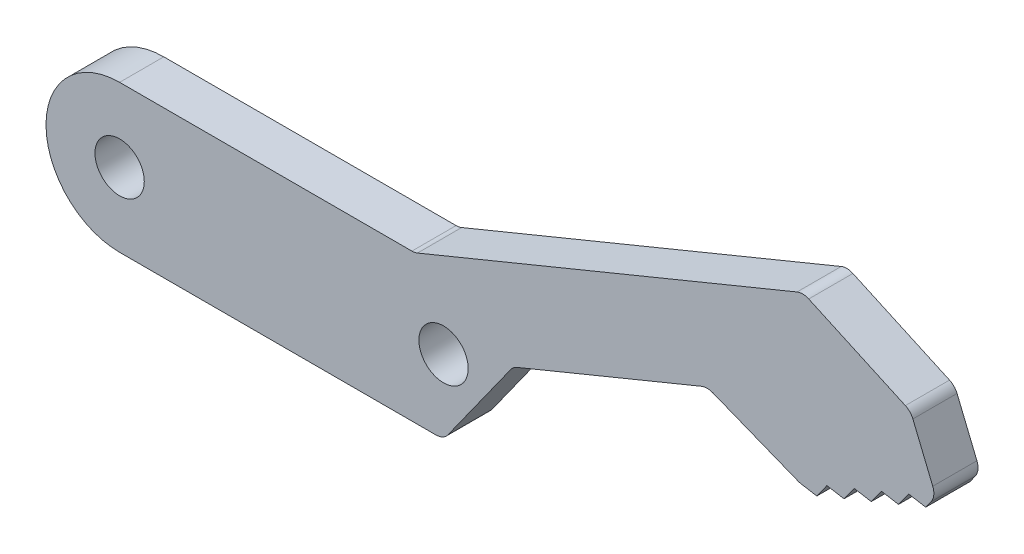
SolidWorks part; units mm, degrees
ref_plane "Front Plane" through (0, 0, 0) normal (0, 0, 1) x (1, 0, 0)
ref_plane "Top Plane" through (0, 0, 0) normal (0, 1, 0) x (1, 0, 0)
ref_plane "Right Plane" through (0, 0, 0) normal (1, 0, 0) x (0, 0, -1)
sketch "Sketch1" plane through (0, 0, 0) normal (0, 0, 1) x (1, 0, 0)
  line L0 (0, 0) -> (22, 0) construction
  line L1 (0, 5) -> (22, 5)
  line L2 (0, -5) -> (22, -5)
  line L3 (20.05, 5) -> (23.9914, -4.5863) construction
  line L4 (20.05, 5) -> (51.4959, 17.929) construction
  line L5 (23.9914, -4.5863) -> (55.4373, 8.3426) construction
  line L6 (51.4959, 17.929) -> (55.4373, 8.3426) construction
  line L7 (20.05, 5) -> (46.409, 15.8375)
  line L8 (46.409, 15.8375) -> (53.7261, 12.5046)
  line L9 (53.7261, 12.5046) -> (55.4373, 8.3426)
  line L10 (55.4373, 8.3426) -> (46.1885, 4.54) construction
  line L11 (46.1885, 4.54) -> (39.9002, 7.0361)
  line L12 (39.9002, 7.0361) -> (26.7299, 1.6211)
  line L13 (46.1885, 4.54) -> (47.351, 4.3422)
  line L14 (47.351, 4.3422) -> (48.0382, 5.3005)
  line L15 (47.351, 4.3422) -> (54.7501, 7.3843) construction
  line L16 (48.0382, 5.3005) -> (49.2008, 5.1027)
  line L17 (49.2008, 5.1027) -> (49.888, 6.0611)
  line L18 (49.888, 6.0611) -> (51.0505, 5.8633)
  line L19 (51.0505, 5.8633) -> (51.7378, 6.8216)
  line L20 (51.7378, 6.8216) -> (52.9003, 6.6238)
  line L21 (52.9003, 6.6238) -> (53.5875, 7.5821)
  line L22 (53.5875, 7.5821) -> (54.7501, 7.3843)
  line L23 (54.7501, 7.3843) -> (55.4373, 8.3426)
  line L24 (26.7299, 1.6211) -> (22, -5)
  arc A0 (0, 5) -> (0, -5) centre (0, 0) ccw
  arc A1 (22, -5) -> (22, 5) centre (22, 0) ccw
  circle A2 centre (0, 0) radius 1.675
  circle A3 centre (22, 0) radius 1.675
  point P3 (11, 0)
  dimension "D11" = 3.35
  dimension "D1" = 10
  dimension "D2" = 22
  dimension "D3" = 157.65
  dimension "D4" = 1.95
  dimension "D5" = 34
  dimension "D6" = 14.24
  dimension "D7" = 10
  dimension "D8" = 4.5
  dimension "D9" = 136
  dimension "D10" = 5.5
  dimension "D12" = 2
  dimension "D13" = 0.625
  dimension "D14" = 8
extrude "Boss-Extrude1" add sketch "Sketch1" along normal blind 3 contours A1 L1 A0 L2 A3 A2 | A1 L12 L11 L13 L14 L16 L17 L18 L19 L20 L21 L22 L23 L9 L8 L7 L1
fillet "Fillet1" radius 1 8 edges at (46.1885, 4.54, 1.5) (55.4373, 8.3426, 1.5) (53.7261, 12.5046, 1.5) (46.409, 15.8375, 1.5) (20.05, 5, 1.5) (39.9002, 7.0361, 1.5) (26.7299, 1.6211, 1.5) (22, -5, 1.5)
